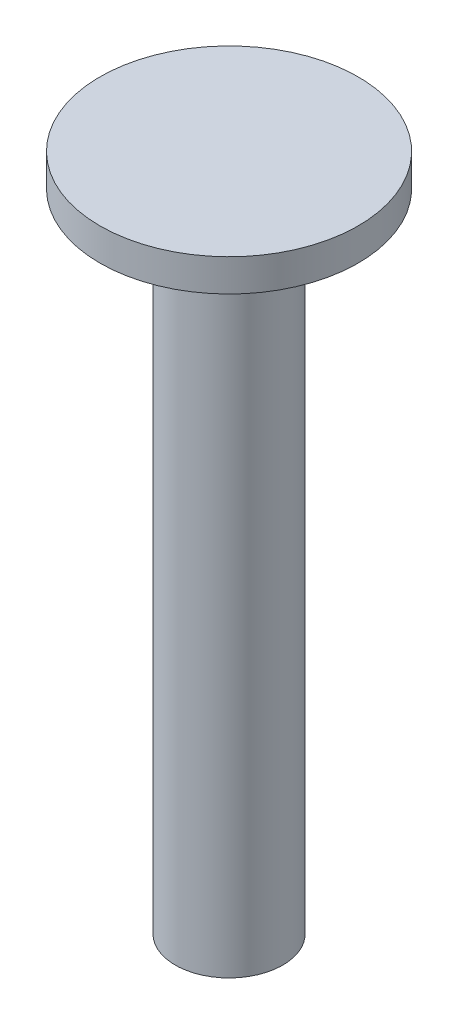
SolidWorks part; units mm, degrees
material "AISI 304"
ref_plane "前视基准面" through (0, 0, 0) normal (0, 0, 1) x (1, 0, 0)
ref_plane "上视基准面" through (0, 0, 0) normal (0, 1, 0) x (1, 0, 0)
ref_plane "右视基准面" through (0, 0, 0) normal (1, 0, 0) x (0, 0, -1)
other "Configuration Table"
sketch "草图1" plane through (0, 0, 0) normal (0, 1, 0) x (1, 0, 0)
  circle A0 centre (0, 0) radius 2.4
  dimension "D1" = 4.8
extrude "凸台-拉伸1" add sketch "草图1" along normal blind 0.6
sketch "草图2" plane through (0, 0, 0) normal (0, -1, 0) x (1, 0, 0)
  circle A0 centre (0, 0) radius 1
  dimension "D1" = 2
extrude "凸台-拉伸2" add sketch "草图2" along normal blind 12
